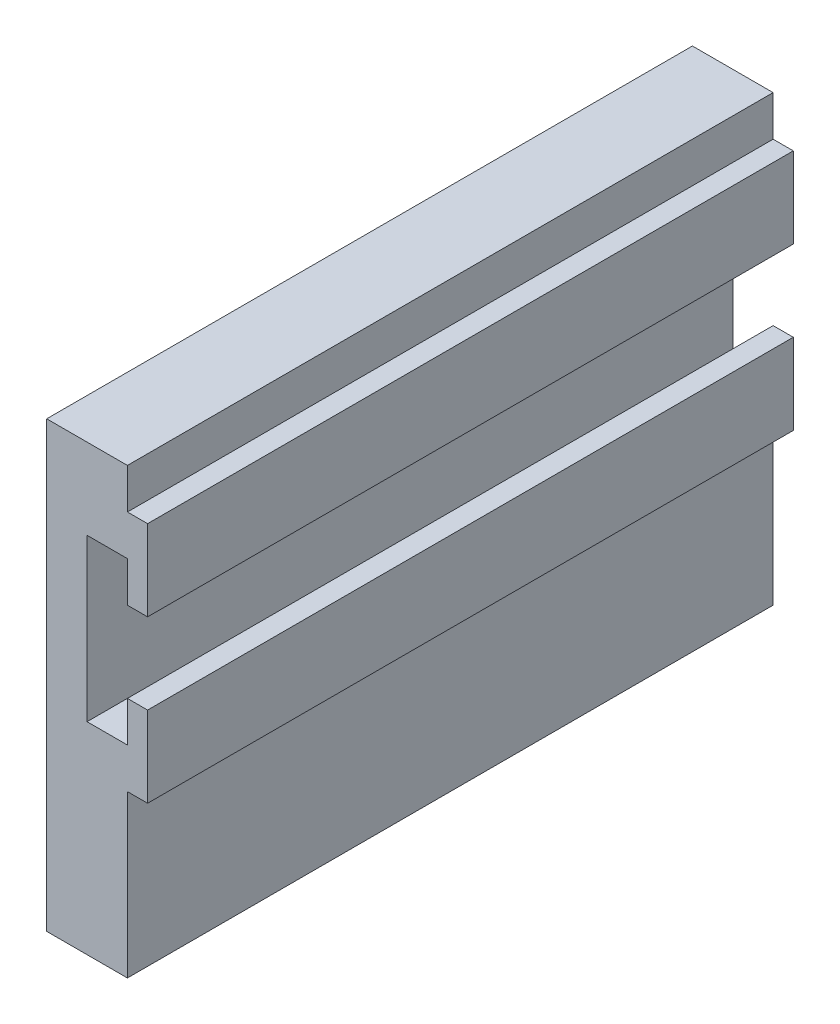
SolidWorks part; units mm, degrees
ref_plane "Front Plane" through (0, 0, 0) normal (0, 0, 1) x (1, 0, 0)
ref_plane "Top Plane" through (0, 0, 0) normal (0, 1, 0) x (1, 0, 0)
ref_plane "Right Plane" through (0, 0, 0) normal (1, 0, 0) x (0, 0, -1)
sketch "Sketch1" plane through (0, 0, 0) normal (0, 0, 1) x (1, 0, 0)
  line L0 (0, 0) -> (20, 0)
  line L1 (20, 0) -> (20, 20)
  line L2 (20, 20) -> (10, 20)
  line L3 (10, 20) -> (10, 60)
  line L4 (10, 60) -> (20, 60)
  line L5 (20, 60) -> (20, 80)
  line L6 (20, 80) -> (0, 80)
  line L7 (0, 80) -> (0, 0)
  dimension "D1" = 20
  dimension "D2" = 20
  dimension "D3" = 40
  dimension "D4" = 10
  dimension "D5" = 20
  dimension "D6" = 10
extrude "Boss-Extrude1" add sketch "Sketch1" along normal blind 160
sketch "Sketch2" plane through (0, 0, 0) normal (0, -1, 0) x (1, 0, 0)
  line L1 (20, 160) -> (0, 160)
  line L2 (20, 160) -> (20, 0)
  line L3 (20, 0) -> (0, 0)
  line L4 (0, 160) -> (0, 0)
extrude "Boss-Extrude2" add sketch "Sketch2" along normal blind 30
sketch "Sketch3" plane through (0, 20, 0) normal (0, 1, 0) x (1, 0, 0)
  line L1 (20, -160) -> (25, -160)
  line L2 (20, -160) -> (20, 0)
  line L3 (20, 0) -> (25, 0)
  line L4 (25, -160) -> (25, 0)
  dimension "D1" = 5
extrude "Boss-Extrude3" add sketch "Sketch3" along normal blind 10 and the other way blind 10
sketch "Sketch4" plane through (0, 60, 0) normal (0, -1, 0) x (1, 0, 0)
  line L1 (20, 0) -> (25, 0)
  line L2 (20, 0) -> (20, 160)
  line L3 (20, 160) -> (25, 160)
  line L4 (25, 0) -> (25, 160)
  dimension "D1" = 5
extrude "Boss-Extrude4" add sketch "Sketch4" along normal blind 10 and the other way blind 10
